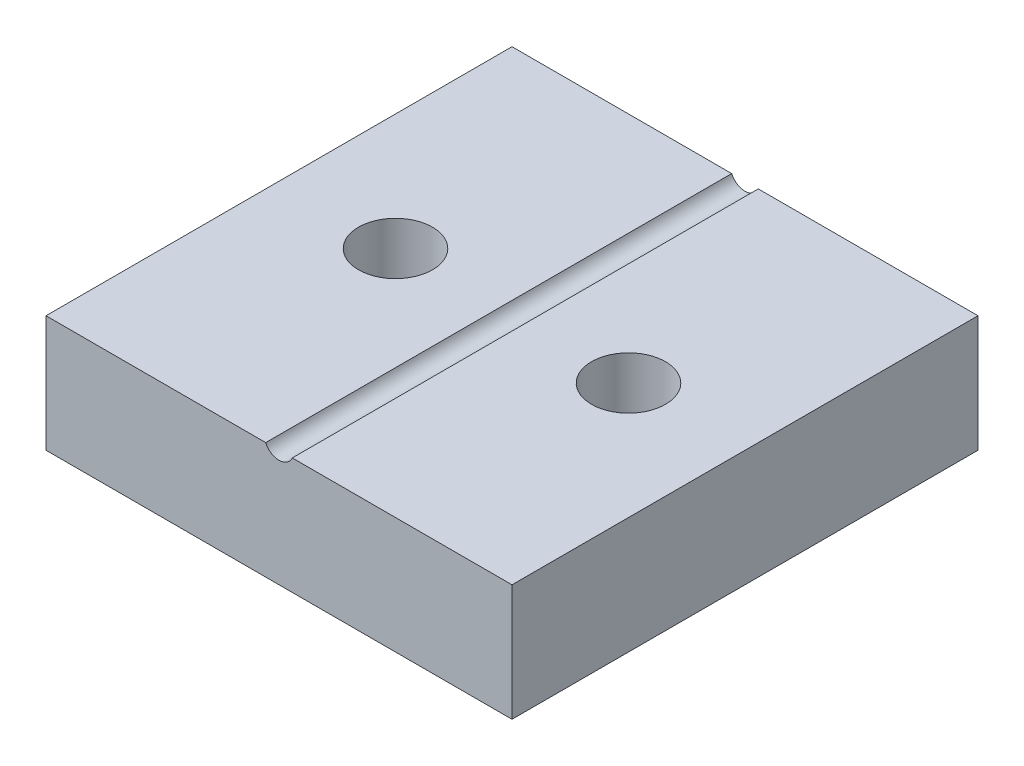
SolidWorks part; units mm, degrees
ref_plane "Front Plane" through (0, 0, 0) normal (0, 0, 1) x (1, 0, 0)
ref_plane "Top Plane" through (0, 0, 0) normal (0, 1, 0) x (1, 0, 0)
ref_plane "Right Plane" through (0, 0, 0) normal (1, 0, 0) x (0, 0, -1)
sketch "Sketch1" plane through (0, 0, 0) normal (0, 1, 0) x (1, 0, 0)
  line L1 (-60.7547, 52.0755) -> (-40.7547, 52.0755)
  line L2 (-60.7547, 52.0755) -> (-60.7547, 32.0755)
  line L3 (-60.7547, 32.0755) -> (-40.7547, 32.0755)
  line L4 (-40.7547, 52.0755) -> (-40.7547, 32.0755)
  dimension "D1" = 20
  dimension "D2" = 20
extrude "Boss-Extrude1" add sketch "Sketch1" along normal blind 5
sketch "Sketch2" plane through (0, 0, -32.0755) normal (0, 0, 1) x (1, 0, 0)
  line L0 (-60.7547, 5) -> (-40.7547, 5) construction
  line L1 (-50.7547, 6.7696) -> (-50.7547, 3.4135) construction
  circle A0 centre (-50.7547, 5.25) radius 0.6223
  point P6 (-50.7547, 5)
  dimension "D2" = 1.2446
  dimension "D1" = 0.25
extrude "Cut-Extrude1" cut sketch "Sketch2" against normal through all contours A0
sketch "Sketch3" plane through (0, 5, 0) normal (0, 1, 0) x (1, 0, 0)
  line L0 (-55.7547, 42.0755) -> (-45.7547, 42.0755) construction
  line L3 (-60.7547, 52.0755) -> (-40.7547, 32.0755) construction
  line L4 (-40.7547, 52.0755) -> (-60.7547, 32.0755) construction
  circle A0 centre (-55.7547, 42.0755) radius 1.5875
  circle A1 centre (-45.7547, 42.0755) radius 1.5875
  point P2 (-50.7547, 42.0755)
  dimension "D2" = 3.175
  dimension "D1" = 10
extrude "Cut-Extrude2" cut sketch "Sketch3" against normal through all
